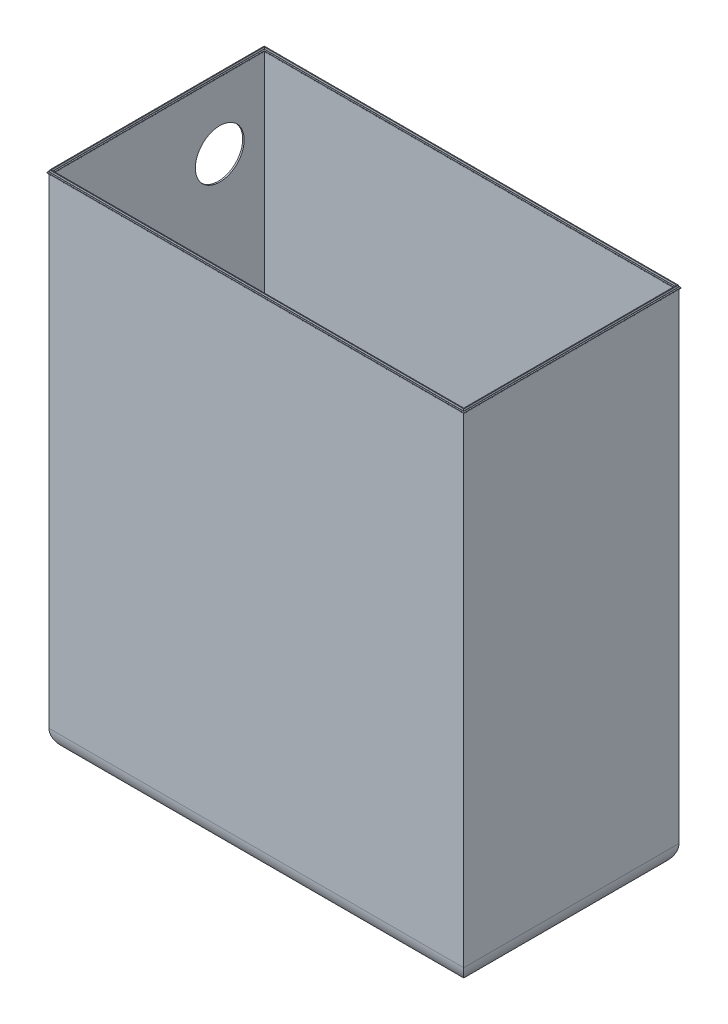
SolidWorks part; units mm, degrees
ref_plane "Front Plane" through (0, 0, 0) normal (0, 0, 1) x (1, 0, 0)
ref_plane "Top Plane" through (0, 0, 0) normal (0, 1, 0) x (1, 0, 0)
ref_plane "Right Plane" through (0, 0, 0) normal (1, 0, 0) x (0, 0, -1)
sketch "Sketch1" plane through (0, 0, 0) normal (0, 0, 1) x (1, 0, 0)
  line L1 (0, 0) -> (289, 0)
  line L2 (0, 0) -> (0, 350)
  line L3 (0, 350) -> (289, 350)
  line L4 (289, 0) -> (289, 350)
  dimension "D1" = 289
  dimension "D2" = 350
extrude "Boss-Extrude1" add sketch "Sketch1" against normal mid plane 150
fillet "Fillet1" radius 15 4 edges at (144.5, 0, -75) (144.5, 0, 75) (0, 0, 0) (289, 0, 0)
shell "Shell1" thickness 1
sketch "Sketch3" plane through (0, 350, 0) normal (0, 1, 0) x (1, 0, 0)
  line L14 (288.5, -74.5) -> (288.5, 74.5)
  line L15 (0.5, -74.5) -> (288.5, -74.5)
  line L16 (0.5, 74.5) -> (0.5, -74.5)
  line L17 (288.5, 74.5) -> (0.5, 74.5)
  line L18 (288.5, -74.5) -> (288.5, 74.5)
  line L19 (0.5, -74.5) -> (288.5, -74.5)
  line L20 (0.5, 74.5) -> (0.5, -74.5)
  line L21 (288.5, 74.5) -> (0.5, 74.5)
  dimension "D1" = 0.5
sketch "Sketch4" plane through (0, 0, 0) normal (0, 0, 1) x (1, 0, 0)
  line L0 (-0.65, 350) -> (1.65, 350)
  line L3 (-0.75, 350.1) -> (-0.75, 350.4)
  line L4 (-0.65, 350.5) -> (0.15, 350.5)
  line L5 (0.25, 350.6) -> (0.25, 351.9)
  line L6 (0.35, 352) -> (0.65, 352)
  line L7 (0.75, 351.9) -> (0.75, 350.6)
  line L8 (0.85, 350.5) -> (1.65, 350.5)
  line L9 (1.75, 350.4) -> (1.75, 350.1)
  arc A0 (1.75, 350.1) -> (1.65, 350) centre (1.65, 350.1) cw
  arc A1 (1.75, 350.4) -> (1.65, 350.5) centre (1.65, 350.4) ccw
  arc A2 (0.85, 350.5) -> (0.75, 350.6) centre (0.85, 350.6) cw
  arc A3 (0.25, 350.6) -> (0.15, 350.5) centre (0.15, 350.6) cw
  arc A4 (-0.65, 350.5) -> (-0.75, 350.4) centre (-0.65, 350.4) ccw
  arc A5 (-0.65, 350) -> (-0.75, 350.1) centre (-0.65, 350.1) cw
  arc A6 (0.75, 351.9) -> (0.65, 352) centre (0.65, 351.9) ccw
  arc A7 (0.35, 352) -> (0.25, 351.9) centre (0.35, 351.9) ccw
  point P4 (0.5, 350)
  point P7 (0.75, 352)
  point P19 (1.75, 350.5)
  point P22 (0.75, 350.5)
  point P25 (0.25, 350.5)
  point P33 (0.25, 352)
  dimension "D5" = 0.1
  dimension "D2" = 0.1
  dimension "D1" = 0.5
  dimension "D3" = 2
  dimension "D4" = 0.5
  dimension "D6" = 2.5
sweep "Sweep1" add profiles "Sketch4" path "Sketch3"
sketch "Sketch5" plane through (0, 0, 0) normal (0, -1, 0) x (1, 0, 0)
  circle A0 centre (243.1286, 0) radius 18
  dimension "D1" = 36
extrude "Cut-Extrude1" cut sketch "Sketch5" against normal blind 10
sketch "Sketch6" plane through (0, 0, 0) normal (-1, 0, 0) x (0, 0, 1)
  line L0 (-75, 350) -> (-75, 15) construction
  line L1 (-75.75, 350.1) -> (0, 350.1) construction
  circle A0 centre (-43, 303.1) radius 17
  dimension "D1" = 34
  dimension "D2" = 32
  dimension "D3" = 47
extrude "Cut-Extrude2" cut sketch "Sketch6" against normal blind 10
